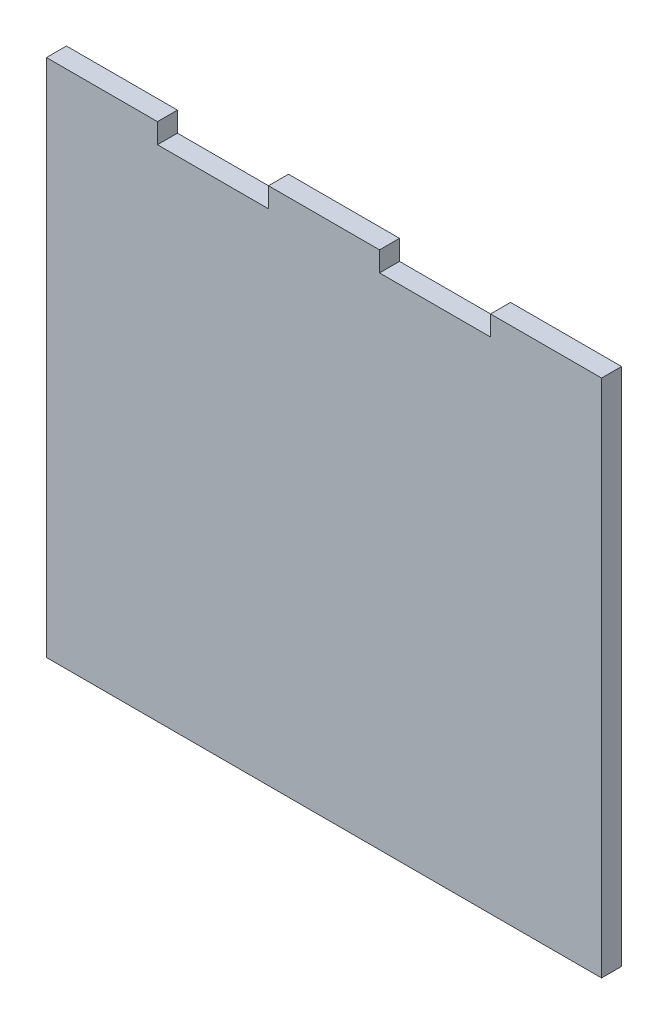
SolidWorks part; units mm, degrees
ref_plane "Front Plane" through (0, 0, 0) normal (0, 0, 1) x (1, 0, 0)
ref_plane "Top Plane" through (0, 0, 0) normal (0, 1, 0) x (1, 0, 0)
ref_plane "Right Plane" through (0, 0, 0) normal (1, 0, 0) x (0, 0, -1)
sketch "Sketch1" plane through (0, 0, 0) normal (0, 0, 1) x (1, 0, 0)
  line L1 (0, 0) -> (127, 0)
  line L2 (0, 0) -> (0, 118.872)
  line L3 (0, 118.872) -> (127, 118.872)
  line L4 (127, 0) -> (127, 118.872)
  dimension "D1" = 127
  dimension "D2" = 118.872
extrude "Boss-Extrude1" add sketch "Sketch1" along normal blind 4.572
sketch "Sketch2" plane through (0, 0, 4.572) normal (0, 0, 1) x (1, 0, 0)
  line L0 (127, 118.872) -> (0, 118.872) construction
  line L1 (25.4, 118.872) -> (50.8, 118.872)
  line L2 (25.4, 118.872) -> (25.4, 114.3)
  line L3 (25.4, 114.3) -> (50.8, 114.3)
  line L4 (50.8, 118.872) -> (50.8, 114.3)
  line L5 (0, 118.872) -> (0, 0) construction
  line L6 (76.2, 118.872) -> (101.6, 118.872)
  line L7 (76.2, 118.872) -> (76.2, 114.3)
  line L8 (76.2, 114.3) -> (101.6, 114.3)
  line L9 (101.6, 118.872) -> (101.6, 114.3)
  dimension "D1" = 4.572
  dimension "D2" = 4.572
  dimension "D3" = 25.4
  dimension "D4" = 25.4
  dimension "D5" = 25.4
  dimension "D6" = 25.4
extrude "Cut-Extrude1" cut sketch "Sketch2" against normal blind 4.572
equation "\"D1@Boss-Extrude1\"=0.18in"
